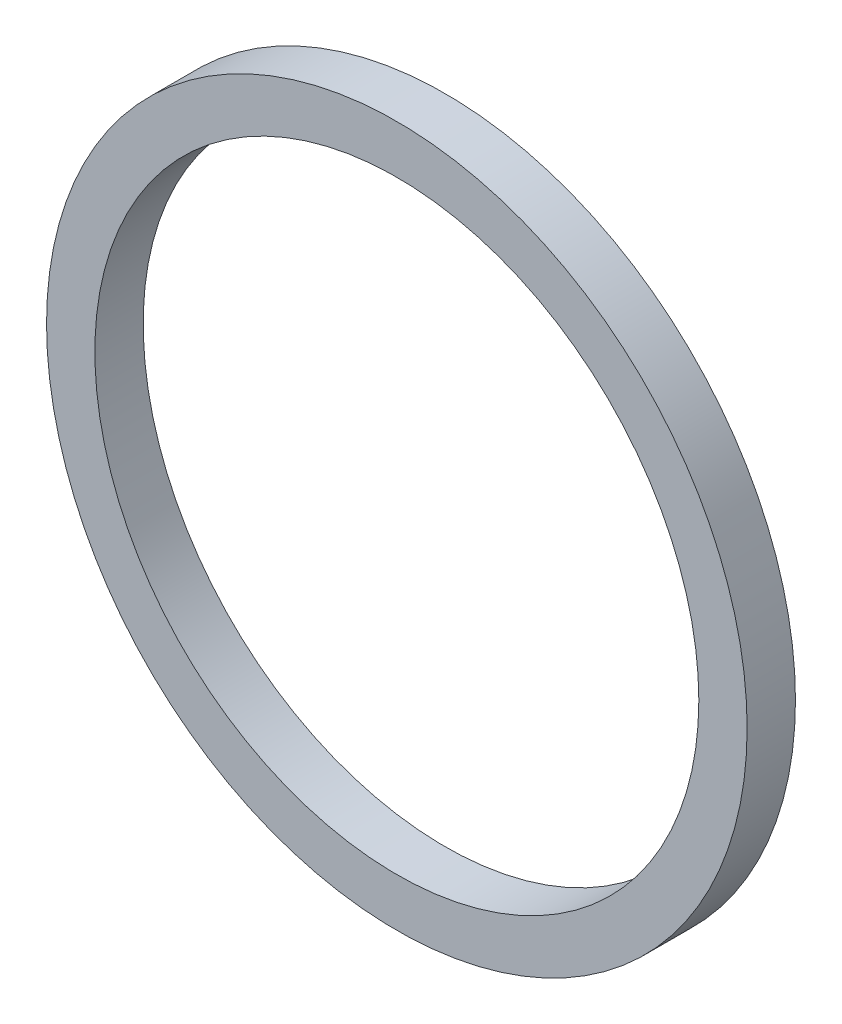
SolidWorks part; units mm, degrees
ref_plane "Front Plane" through (0, 0, 0) normal (0, 0, 1) x (1, 0, 0)
ref_plane "Top Plane" through (0, 0, 0) normal (0, 1, 0) x (1, 0, 0)
ref_plane "Right Plane" through (0, 0, 0) normal (1, 0, 0) x (0, 0, -1)
sketch "Sketch1" plane through (0, 0, 0) normal (0, 0, 1) x (1, 0, 0)
  circle A0 centre (0, 0) radius 12.5
  circle A1 centre (0, 0) radius 14.5
  dimension "D1" = 25
  dimension "D2" = 2
extrude "Boss-Extrude1" add sketch "Sketch1" along normal blind 2
